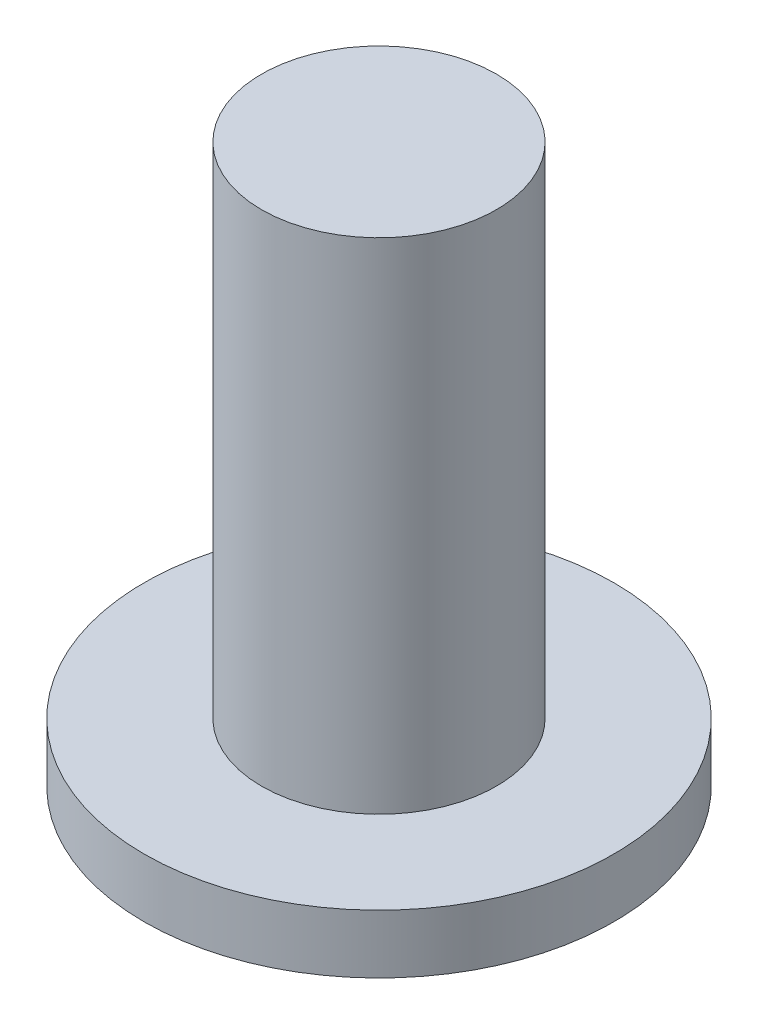
SolidWorks part; units mm, degrees
ref_plane "Front Plane" through (0, 0, 0) normal (0, 0, 1) x (1, 0, 0)
ref_plane "Top Plane" through (0, 0, 0) normal (0, 1, 0) x (1, 0, 0)
ref_plane "Right Plane" through (0, 0, 0) normal (1, 0, 0) x (0, 0, -1)
sketch "Sketch2" plane through (0, 0, 0) normal (1, 0, 0) x (0, 0, -1)
  line L0 (0, 293.9203) -> (0, -295.5975) construction
  line L1 (-100, 225) -> (0, 225)
  line L2 (-100, 225) -> (-100, -200)
  line L3 (-100, -200) -> (-200, -200)
  line L4 (-200, -200) -> (-200, -250)
  line L5 (-200, -250) -> (0, -250)
  line L6 (0, -250) -> (0, 225)
  dimension "D1" = 225
  dimension "D2" = 200
  dimension "D3" = 425
  dimension "D4" = 50
  dimension "D5" = 200
  dimension "D6" = 100
  dimension "D7" = 100
revolve "Revolve1" add sketch "Sketch2" angle 360 about L0
